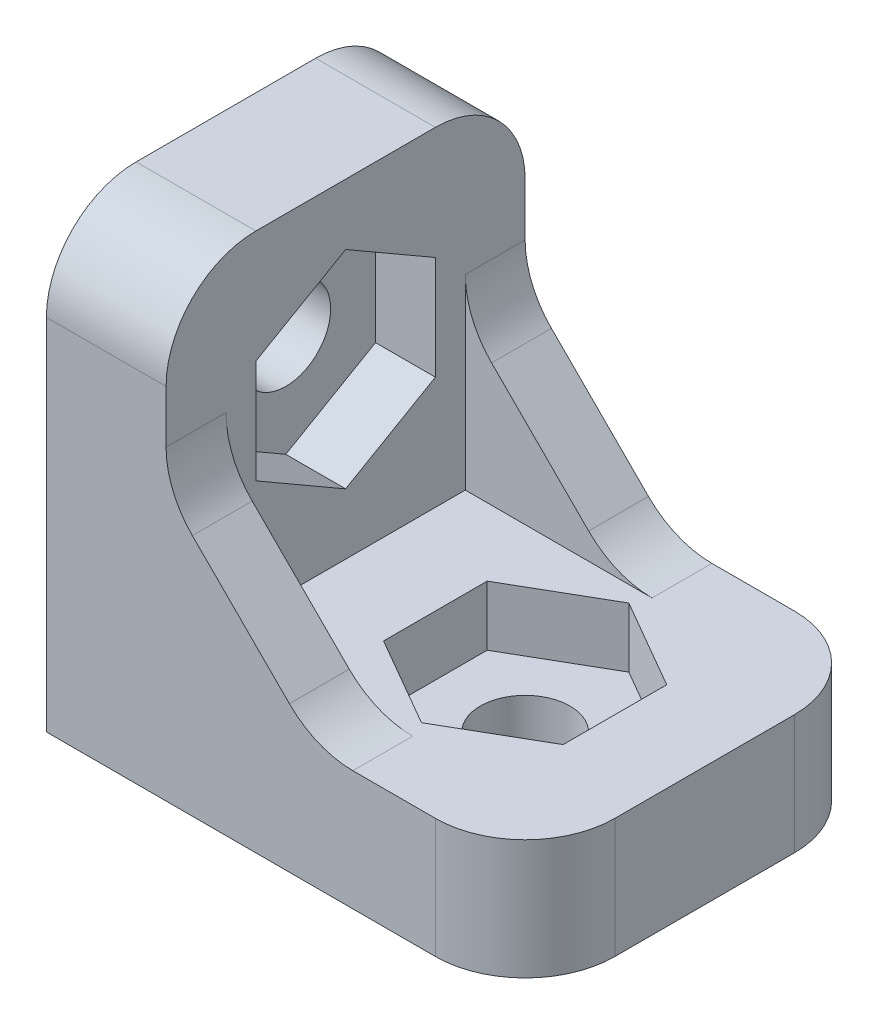
SolidWorks part; units mm, degrees
ref_plane "Front Plane" through (0, 0, 0) normal (0, 0, 1) x (1, 0, 0)
ref_plane "Top Plane" through (0, 0, 0) normal (0, 1, 0) x (1, 0, 0)
ref_plane "Right Plane" through (0, 0, 0) normal (1, 0, 0) x (0, 0, -1)
sketch "Sketch1" plane through (0, 0, 0) normal (0, 0, 1) x (1, 0, 0)
  line L0 (0, 0) -> (0, 15)
  line L1 (0, 15) -> (4, 15)
  line L2 (4, 15) -> (4, 4)
  line L3 (4, 4) -> (16, 4)
  line L4 (16, 4) -> (16, 0)
  line L5 (16, 0) -> (0, 0)
  dimension "D1" = 4
  dimension "D2" = 4
  dimension "D3" = 16
  dimension "D4" = 15
extrude "Boss-Extrude1" add sketch "Sketch1" along normal blind 12
sketch "Sketch2" plane through (4, 0, 0) normal (1, 0, 0) x (0, 0, -1)
  circle A0 centre (-6, 9.5) radius 1.5
  dimension "D1" = 3
extrude "Cut-Extrude1" cut sketch "Sketch2" against normal through all
sketch "Sketch3" plane through (4, 0, 0) normal (1, 0, 0) x (0, 0, -1)
  line L1 (-6, 12.9641) -> (-9, 11.2321)
  line L2 (-9, 11.2321) -> (-9, 7.7679)
  line L3 (-9, 7.7679) -> (-6, 6.0359)
  line L4 (-6, 6.0359) -> (-3, 7.7679)
  line L5 (-3, 7.7679) -> (-3, 11.2321)
  line L6 (-3, 11.2321) -> (-6, 12.9641)
  circle A0 centre (-6, 9.5) radius 3 construction
extrude "Cut-Extrude2" cut sketch "Sketch3" against normal blind 2
sketch "Sketch4" plane through (0, 0, 0) normal (0, -1, 0) x (1, 0, 0)
  line L0 (0, 12) -> (0, 0) construction
  circle A0 centre (10, 6) radius 1.5
  dimension "D1" = 3
  dimension "D2" = 10
extrude "Cut-Extrude3" cut sketch "Sketch4" against normal through all
sketch "Sketch5" plane through (0, 4, 0) normal (0, 1, 0) x (1, 0, 0)
  line L0 (0, -12) -> (0, 0) construction
  line L1 (10, -9.4641) -> (13, -7.7321)
  line L2 (13, -7.7321) -> (13, -4.2679)
  line L3 (13, -4.2679) -> (10, -2.5359)
  line L4 (10, -2.5359) -> (7, -4.2679)
  line L5 (7, -4.2679) -> (7, -7.7321)
  line L6 (7, -7.7321) -> (10, -9.4641)
  circle A0 centre (10, -6) radius 3 construction
  point P11 (0, 0)
  dimension "D1" = 10
extrude "Cut-Extrude4" cut sketch "Sketch5" against normal blind 2
sketch "Sketch6" plane through (0, 0, 0) normal (0, 0, -1) x (-1, 0, 0)
  line L0 (-4, 4) -> (-4, 9)
  line L1 (-4, 4) -> (-4, 15) construction
  line L2 (-4, 9) -> (-9, 4)
  line L3 (-16, 4) -> (-4, 4) construction
  line L4 (-9, 4) -> (-4, 4)
  dimension "D1" = 5
  dimension "D2" = 5
extrude "Boss-Extrude2" add sketch "Sketch6" against normal blind 2
sketch "Sketch7" plane through (0, 0, 12) normal (0, 0, 1) x (1, 0, 0)
  line L3 (4, 9) -> (4, 4)
  line L4 (9, 4) -> (4, 9)
  line L5 (4, 4) -> (9, 4)
  line L6 (4, 9) -> (4, 4)
  line L7 (9, 4) -> (4, 9)
  line L8 (4, 4) -> (9, 4)
  dimension "D1" = 0
extrude "Boss-Extrude3" add sketch "Sketch7" against normal blind 2
fillet "Fillet1" radius 3 8 edges at (9, 4, 11) (4, 9, 11) (4, 9, 1) (9, 4, 1) (16, 2, 0) (16, 2, 12) (2, 15, 12) (2, 15, 0)
